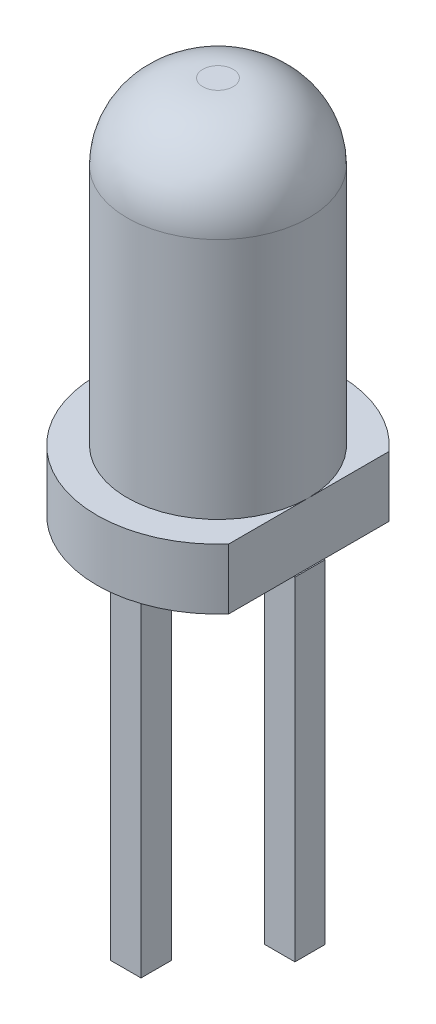
SolidWorks part; units mm, degrees
ref_plane "Alzado" through (0, 0, 0) normal (0, 0, 1) x (1, 0, 0)
ref_plane "Planta" through (0, 0, 0) normal (0, 1, 0) x (1, 0, 0)
ref_plane "Vista lateral" through (0, 0, 0) normal (1, 0, 0) x (0, 0, -1)
sketch "Croquis1" plane through (0, 0, 0) normal (0, 1, 0) x (1, 0, 0)
  circle A0 centre (0, 0) radius 2
  dimension "D1" = 4
extrude "Base" add sketch "Croquis1" along normal blind 1
sketch "Croquis2" plane through (0, 1, 0) normal (0, 1, 0) x (1, 0, 0)
  circle A0 centre (0, 0) radius 1.5
  dimension "D1" = 3
extrude "Cuerpo del LED" add sketch "Croquis2" along normal blind 5.25
sketch "Croquis3" plane through (0, 0, 0) normal (0, -1, 0) x (1, 0, 0)
  line L0 (-1.2701, 0) -> (0, 0) construction
  line L1 (0, 0) -> (1.2702, 0) construction
  line L2 (-1.5201, -0.25) -> (-1.0201, 0.25) construction
  line L3 (-1.5201, -0.25) -> (-1.0201, -0.25)
  line L4 (-1.5201, -0.25) -> (-1.5201, 0.25)
  line L5 (-1.5201, 0.25) -> (-1.0201, 0.25)
  line L6 (-1.0201, -0.25) -> (-1.0201, 0.25)
  line L7 (1.0202, -0.25) -> (1.5202, 0.25) construction
  line L8 (1.0202, -0.25) -> (1.5202, -0.25)
  line L9 (1.0202, -0.25) -> (1.0202, 0.25)
  line L10 (1.0202, 0.25) -> (1.5202, 0.25)
  line L11 (1.5202, -0.25) -> (1.5202, 0.25)
  dimension "D1" = 0.5
  dimension "D2" = 0.5
  dimension "D3" = 0.5
  dimension "D4" = 0.5
extrude "Pines" add sketch "Croquis3" along normal blind 7 from vertex at 0 starting at point (1.0202, 0, 0.25)
sketch "Croquis4" plane through (0, -7, 0) normal (0, -1, 0) x (1, 0, 0)
  line L4 (1.0202, 0.25) -> (1.0202, -0.25)
  line L5 (1.0202, -0.25) -> (1.5202, -0.25)
  line L6 (1.5202, -0.25) -> (1.5202, 0.25)
  line L7 (1.5202, 0.25) -> (1.0202, 0.25)
  line L8 (1.0202, 0.25) -> (1.0202, -0.25)
  line L9 (1.0202, -0.25) -> (1.5202, -0.25)
  line L10 (1.5202, -0.25) -> (1.5202, 0.25)
  line L11 (1.5202, 0.25) -> (1.0202, 0.25)
  dimension "D1" = 0
extrude "Corte a Catodo" cut sketch "Croquis4" against normal blind 1.5
sketch "Croquis6" plane through (0, 1, 0) normal (0, 1, 0) x (1, 0, 0)
  line L0 (2, 0) -> (1.5, 0) construction
  line L1 (1.5, 2.7304) -> (1.5, -1.7696)
  line L2 (1.5, -1.7696) -> (2.5, -1.7696)
  line L3 (2.5, -1.7696) -> (2.5, 2.7304)
  line L4 (2.5, 2.7304) -> (1.5, 2.7304)
  circle A0 centre (0, 0) radius 2 construction
  circle A1 centre (0, 0) radius 1.5 construction
  dimension "D1" = 4.5
  dimension "D2" = 1
extrude "Ranura" cut sketch "Croquis6" against normal up to surface (1 mm away) up to face at (-1.2701, 0, 0)
fillet "Punta del Led" radius 1.25 1 edges at (0, 6.25, 1.5)
